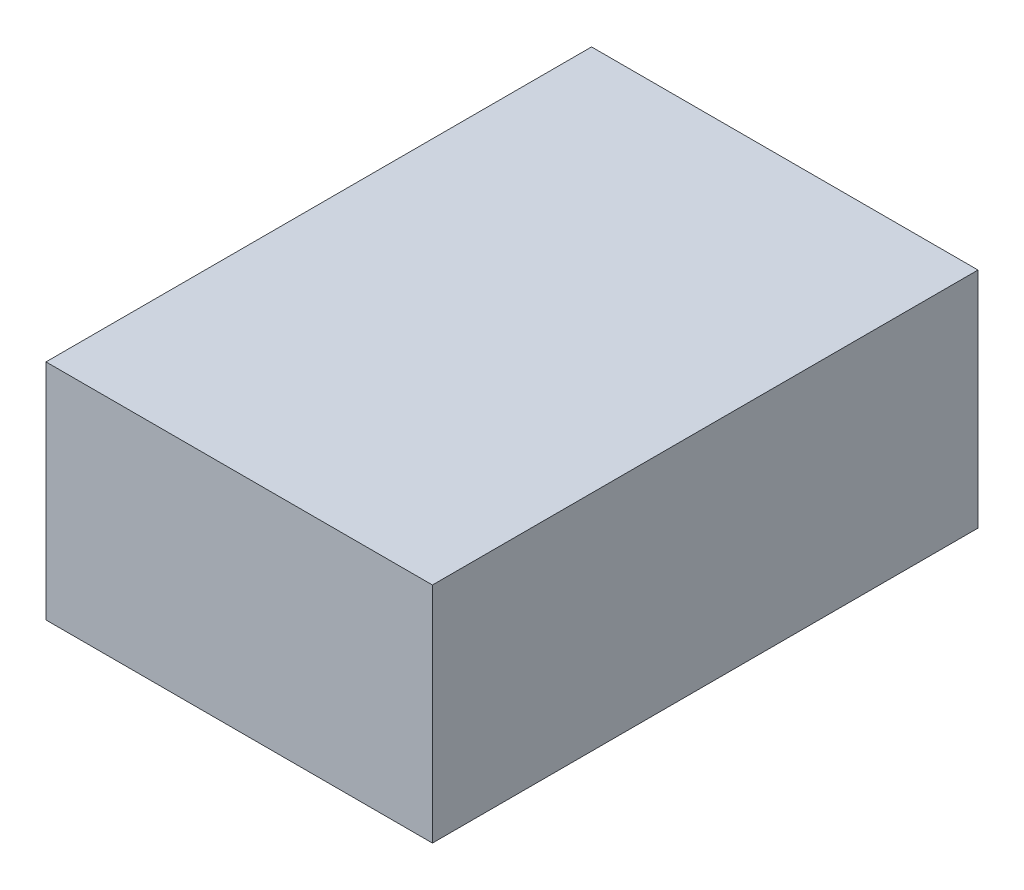
SolidWorks part; units mm, degrees
ref_plane "Front Plane" through (0, 0, 0) normal (0, 0, 1) x (1, 0, 0)
ref_plane "Top Plane" through (0, 0, 0) normal (0, 1, 0) x (1, 0, 0)
ref_plane "Right Plane" through (0, 0, 0) normal (1, 0, 0) x (0, 0, -1)
sketch "Sketch1" plane through (0, 0, 0) normal (0, 1, 0) x (1, 0, 0)
  line L1 (-5.1, -7.2) -> (5.1, -7.2)
  line L2 (-5.1, -7.2) -> (-5.1, 7.2)
  line L3 (-5.1, 7.2) -> (5.1, 7.2)
  line L4 (5.1, -7.2) -> (5.1, 7.2)
  line L5 (-5.1, -7.2) -> (5.1, 7.2) construction
  line L6 (-5.1, 7.2) -> (5.1, -7.2) construction
  point P0 (0, 0)
  dimension "D1" = 14.4
  dimension "D2" = 10.2
extrude "Boss-Extrude1" add sketch "Sketch1" along normal blind 5.9
